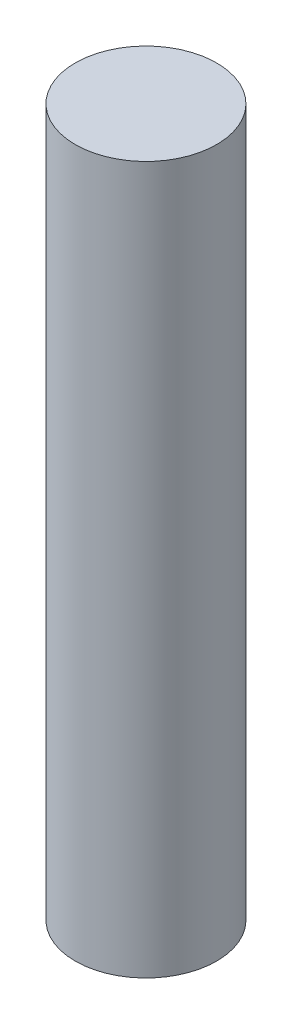
SolidWorks part; units mm, degrees
ref_plane "前视基准面" through (0, 0, 0) normal (0, 0, 1) x (1, 0, 0)
ref_plane "上视基准面" through (0, 0, 0) normal (0, 1, 0) x (1, 0, 0)
ref_plane "右视基准面" through (0, 0, 0) normal (1, 0, 0) x (0, 0, -1)
other "Configuration Table"
sketch "草图1" plane through (0, 0, 0) normal (0, 1, 0) x (1, 0, 0)
  circle A0 centre (0, 0) radius 150
  dimension "D1" = 300
extrude "凸台-拉伸1" add sketch "草图1" along normal blind 1500
